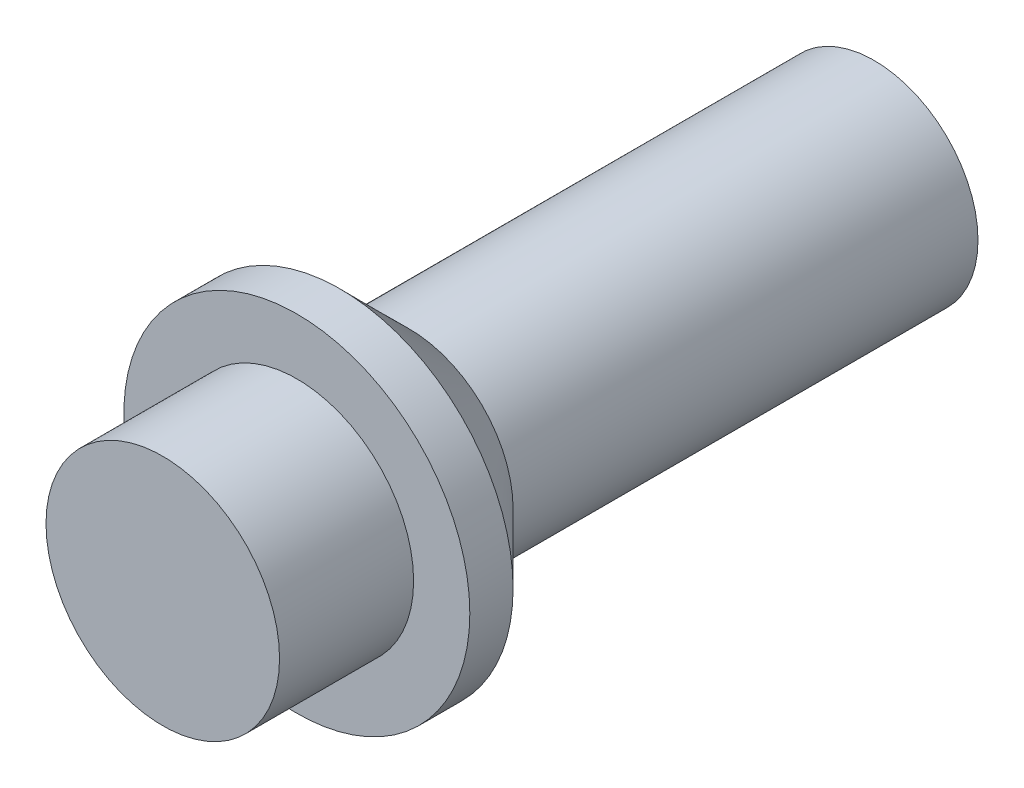
SolidWorks part; units mm, degrees
ref_plane "前视基准面" through (0, 0, 0) normal (0, 0, 1) x (1, 0, 0)
ref_plane "上视基准面" through (0, 0, 0) normal (0, 1, 0) x (1, 0, 0)
ref_plane "右视基准面" through (0, 0, 0) normal (1, 0, 0) x (0, 0, -1)
other "Configuration Table"
sketch "草图1" plane through (0, 0, 0) normal (0, 0, 1) x (1, 0, 0)
  circle A0 centre (0, 0) radius 2.4
extrude "Plunger_stem" add sketch "草图1" along normal blind 10.75 from offset 24.25
sketch "草图2" plane through (0, 0, 0) normal (0, 0, 1) x (1, 0, 0)
  circle A0 centre (0, 0) radius 2.4
extrude "Printable_flange_ramp" add sketch "草图2" along normal blind 1.6 draft 45 from offset 35 draft outward yes
sketch "草图3" plane through (0, 0, 0) normal (0, 0, 1) x (1, 0, 0)
  circle A0 centre (0, 0) radius 4
extrude "Captive_flange" add sketch "草图3" along normal blind 1 from offset 36.6
sketch "草图4" plane through (0, 0, 0) normal (0, 0, 1) x (1, 0, 0)
  circle A0 centre (0, 0) radius 2.7
extrude "Exposed_key_cap" add sketch "草图4" along normal blind 3.1 from offset 37.6
